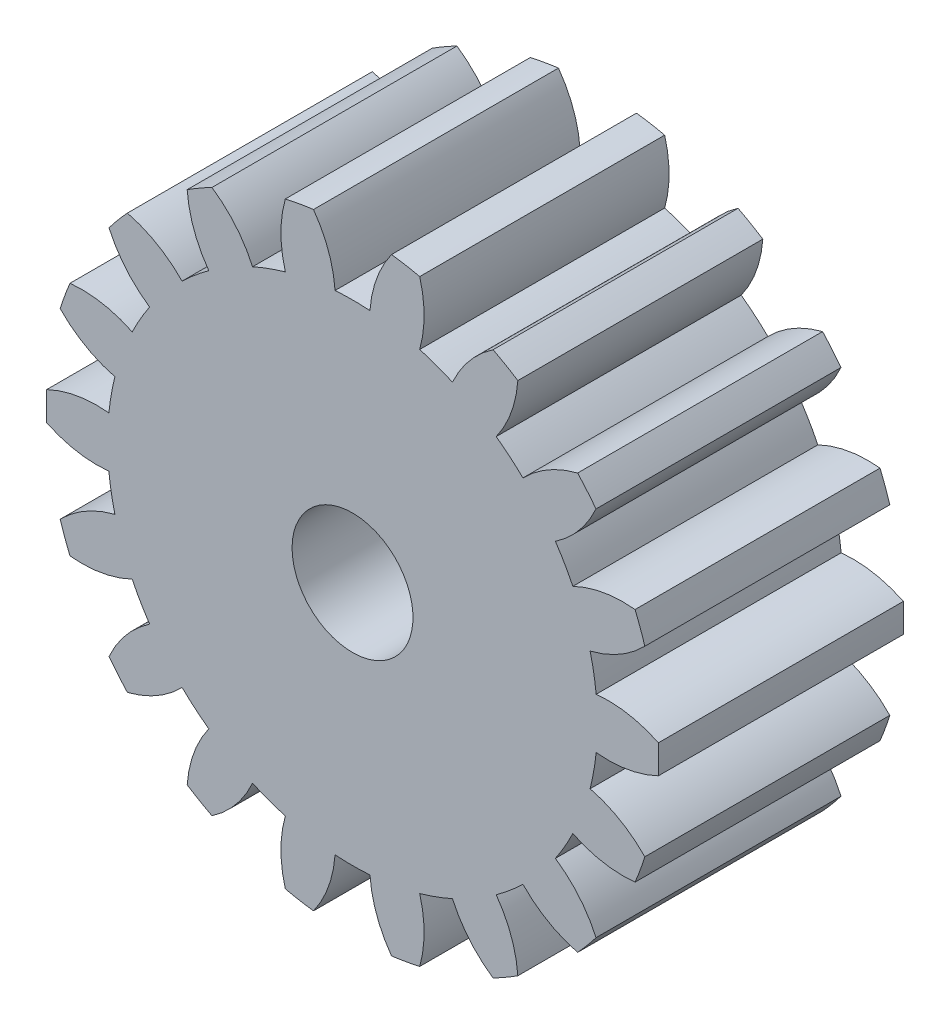
SolidWorks part; units mm, degrees
material "6061 Alloy"
ref_plane "Front Plane" through (0, 0, 0) normal (0, 0, 1) x (1, 0, 0)
ref_plane "Top Plane" through (0, 0, 0) normal (0, 1, 0) x (1, 0, 0)
ref_plane "Right Plane" through (0, 0, 0) normal (1, 0, 0) x (0, 0, -1)
sketch "Sketch1" plane through (0, 0, 0) normal (0, 0, 1) x (1, 0, 0)
  circle A0 centre (0, 0) radius 7.9375
  dimension "D1" = 15.875
extrude "Outer Circle" add sketch "Sketch1" along normal blind 6.35
sketch "Sketch2" plane through (0, 0, 6.35) normal (0, 0, 1) x (1, 0, 0)
  line L0 (0.625, 7.1437) -> (-0.625, 7.1437) construction
  line L1 (1.856, 6.9267) -> (0.625, 7.1437) construction
  line L2 (0, 7.1437) -> (0, 0) construction
  line L3 (0, 0) -> (1.2405, 7.0352) construction
  line L4 (-0.8955, 7.8868) -> (0, 5.4266) construction
  line L5 (0, 5.4266) -> (0.8955, 7.8868) construction
  line L6 (-0.4522, 6.3339) -> (0, 0) construction
  circle A0 centre (0, 0) radius 6.35 construction
  circle A1 centre (0, 0) radius 7.1438 construction
  arc A2 (-0.4522, 6.3339) -> (0.4522, 6.3339) centre (0, 0) cw
  arc A3 (-1.0115, 7.8728) -> (1.0115, 7.8728) centre (0, 0) cw
  circle A4 centre (0, 0) radius 7.9375 construction
  arc A5 (-1.0115, 7.8728) -> (-0.4522, 6.3339) centre (-3.4353, 6.1209) cw
  arc A6 (0.4522, 6.3339) -> (1.0115, 7.8728) centre (3.4353, 6.1209) cw
  point P7 (0, 7.1437)
  point P10 (1.2405, 7.0352)
  point P17 (0, 6.35)
  point P19 (0, 7.9375)
  dimension "D1" = 12.7
  dimension "D2" = 14.2875
  dimension "D3" = 10
  dimension "D4" = 20
extrude "Tooth Cut" cut sketch "Sketch2" against normal through all
pattern_circular "Teeth Pattern" count 18 over 360 about axis through (0, 0, 0) along (0, 0, 1) of "Tooth Cut"
ref_plane "Plane1" through (0, 0, 3.175) normal (0, 0, 1) x (1, 0, 0)
sketch "Pitch Diameter" plane through (0, 0, 3.175) normal (0, 0, 1) x (1, 0, 0)
  circle A0 centre (0, 0) radius 7.1438 construction
  circle A1 centre (0, 0) radius 7.1438
sketch "Sketch3" plane through (0, 0, 0) normal (0, 0, -1) x (-1, 0, 0)
  circle A0 centre (0, 0) radius 1.5672
  dimension "D1" = 3.1344
extrude "Cut-Extrude1" cut sketch "Sketch3" against normal through all
equation "\"No. of Teeth\"= 18"
equation "\"Module\"= 1 / 32'Inverse of Pitch"
equation "\"D1@Sketch1\"=(\"No. of Teeth\"+2)*\"Module\""
equation "\"D1@Sketch2\"=(\"No. of Teeth\"-2)*\"Module\""
equation "\"D2@Sketch2\"= \"No. of Teeth\" * \"Module\"'Pitch Diameter"
equation "\"D3@Sketch2\"=180/\"No. of Teeth\""
equation "\"D1@Teeth Pattern\" = \"No. of Teeth\""
